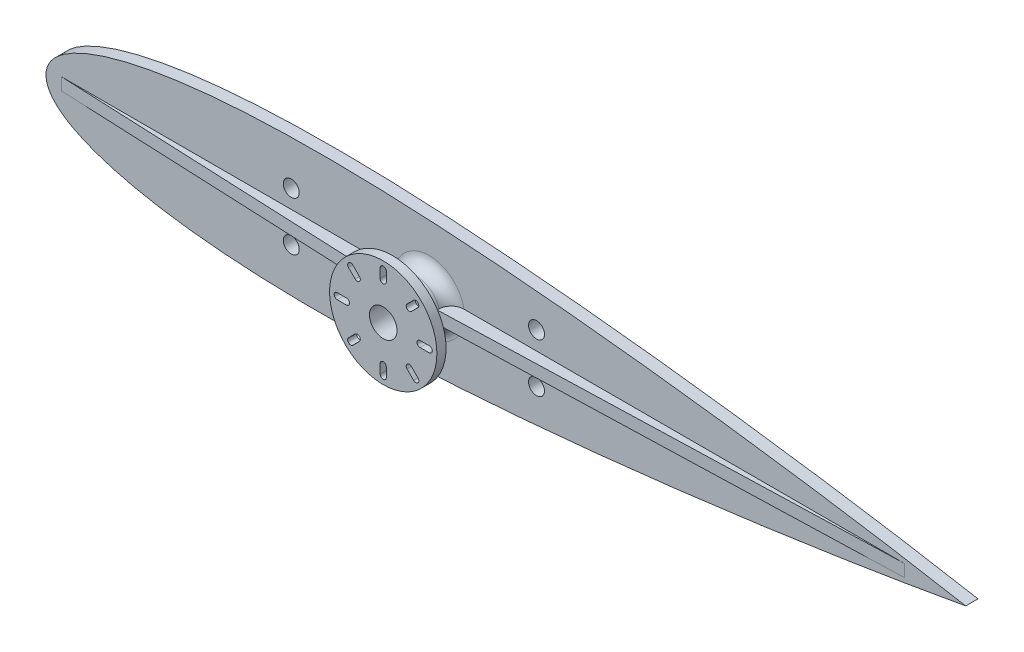
SolidWorks part; units mm, degrees
ref_plane "前视基准面" through (0, 0, 0) normal (0, 0, 1) x (1, 0, 0)
ref_plane "上视基准面" through (0, 0, 0) normal (0, 1, 0) x (1, 0, 0)
ref_plane "右视基准面" through (0, 0, 0) normal (1, 0, 0) x (0, 0, -1)
sketch "草图1" plane through (0, 0, 0) normal (0, 0, 1) x (1, 0, 0)
  line L0 (0, 0) -> (300, 0) construction
  circle A0 centre (125, 0) radius 4.5
  circle A1 centre (80, -8) radius 2.6
  circle A2 centre (160, -8) radius 2.6
  circle A3 centre (80, 8) radius 2.6
  circle A4 centre (160, 8) radius 2.6
  spline S0 degree 4 poles (0, 0) (-0.0001, -0.3264) (0.031, -0.854) (0.1504, -1.6168) (0.4487, -2.6089) (0.8484, -3.53) (1.4338, -4.5344) (2.2636, -5.6397) (3.4568, -6.8967) (5.2259, -8.3759) (7.9066, -10.1418) (11.9899, -12.2256) (18.3217, -14.6656) (27.8261, -17.3002) (41.9741, -19.921) (60.222, -21.8105) (78.6241, -22.5522) (95.989, -22.5497) (113.3459, -22.1022) (130.6895, -21.2711) (148.0103, -20.055) (165.3063, -18.538) (179.7033, -17.1021) (191.211, -15.8592) (201.272, -14.6957) (209.8891, -13.6473) (217.0668, -12.7405) (222.8049, -11.9958) (229.9776, -11.0404) (238.5739, -9.8566) (248.6055, -8.4182) (258.6114, -6.9148) (267.2017, -5.5723) (274.3229, -4.4249) (280.0727, -3.4754) (285.7008, -2.5255) (290.8293, -1.6369) (294.8732, -0.9241) (299.0931, -0.1658) (301.6957, 0.3078) (305.9109, 1.0842) (309.2256, 1.7092) (313.2454, 2.4742) (316.8292, 3.1721) (320.6864, 3.9322) (324.3505, 4.6701) (327.2182, 5.2551) (329.0543, 5.6359) (330.002, 5.8328) knots 0 0 0 0 0 0.003841 0.006235 0.009072 0.012193 0.015657 0.019917 0.025339 0.032593 0.042799 0.057705 0.079311 0.112503 0.158973 0.227236 0.2955 0.329632 0.363764 0.432028 0.500292 0.534424 0.568556 0.602688 0.63682 0.653886 0.670952 0.688018 0.705084 0.739215 0.773347 0.807479 0.824545 0.841611 0.858677 0.875743 0.892809 0.901342 0.909875 0.921141 0.932406 0.943672 0.954938 0.966203 0.977469 0.988734 1 1 1 1 1 construction
  spline S1 degree 4 poles (0, 0) (-0.0001, -0.3264) (0.031, -0.854) (0.1504, -1.6168) (0.4487, -2.6089) (0.8484, -3.53) (1.4338, -4.5344) (2.2636, -5.6397) (3.4568, -6.8967) (5.2259, -8.3759) (7.9066, -10.1418) (11.9899, -12.2256) (18.3217, -14.6656) (27.8261, -17.3002) (41.9741, -19.921) (60.222, -21.8105) (78.6241, -22.5522) (95.989, -22.5497) (113.3459, -22.1022) (130.6895, -21.2711) (148.0103, -20.055) (165.3063, -18.538) (179.7033, -17.1021) (191.211, -15.8592) (201.272, -14.6957) (209.8891, -13.6473) (217.0668, -12.7405) (222.8049, -11.9958) (229.9776, -11.0404) (238.5739, -9.8566) (248.6055, -8.4182) (258.6114, -6.9148) (267.2017, -5.5723) (274.3229, -4.4249) (280.0727, -3.4754) (285.7008, -2.5255) (290.8293, -1.6369) (294.8732, -0.9241) (298.0459, -0.354) (299.3524, -0.1177) (300, 0) knots 0 0 0 0 0 0.003841 0.006235 0.009072 0.012193 0.015657 0.019917 0.025339 0.032593 0.042799 0.057705 0.079311 0.112503 0.158973 0.227236 0.2955 0.329632 0.363764 0.432028 0.500292 0.534424 0.568556 0.602688 0.63682 0.653886 0.670952 0.688018 0.705084 0.739215 0.773347 0.807479 0.824545 0.841611 0.858677 0.875743 0.892809 0.901342 0.909875 0.909875 0.909875 0.909875 0.909875
  spline S2 degree 4 poles (0, 0) (-0.0001, 0.3264) (0.031, 0.854) (0.1504, 1.6168) (0.4487, 2.6089) (0.8484, 3.53) (1.4338, 4.5344) (2.2636, 5.6397) (3.4568, 6.8967) (5.2259, 8.3759) (7.9066, 10.1418) (11.9899, 12.2256) (18.3217, 14.6656) (27.8261, 17.3002) (41.9741, 19.921) (60.222, 21.8105) (78.6241, 22.5522) (95.989, 22.5497) (113.3459, 22.1022) (130.6895, 21.2711) (148.0103, 20.055) (165.3063, 18.538) (179.7033, 17.1021) (191.211, 15.8592) (201.272, 14.6957) (209.8891, 13.6473) (217.0668, 12.7405) (222.8049, 11.9958) (229.9776, 11.0404) (238.5739, 9.8566) (248.6055, 8.4182) (258.6114, 6.9148) (267.2017, 5.5723) (274.3229, 4.4249) (280.0727, 3.4754) (285.7008, 2.5255) (290.8293, 1.6369) (294.8732, 0.9241) (298.0459, 0.354) (299.3524, 0.1177) (300, 0) knots 0 0 0 0 0 0.003841 0.006235 0.009072 0.012193 0.015657 0.019917 0.025339 0.032593 0.042799 0.057705 0.079311 0.112503 0.158973 0.227236 0.2955 0.329632 0.363764 0.432028 0.500292 0.534424 0.568556 0.602688 0.63682 0.653886 0.670952 0.688018 0.705084 0.739215 0.773347 0.807479 0.824545 0.841611 0.858677 0.875743 0.892809 0.901342 0.909875 0.909875 0.909875 0.909875 0.909875
  dimension "D2" = 9
  dimension "D3" = 5.2
  dimension "D6" = 5.2
  dimension "D1" = 125
  dimension "D4" = 8
  dimension "D5" = 80
  dimension "D7" = 8
  dimension "D8" = 80
extrude "凸台-拉伸1" add sketch "草图1" along normal blind 4
sketch "草图2" plane through (0, 0, 4) normal (0, 0, 1) x (1, 0, 0)
  circle A0 centre (125, 0) radius 4.5
  circle A1 centre (125, 0) radius 7.5
  dimension "D1" = 15
  dimension "D2" = 9
extrude "凸台-拉伸2" add sketch "草图2" along normal blind 12
sketch "草图4" plane through (0, 0, 0) normal (0, 1, 0) x (1, 0, 0)
  line L0 (119.5, -9) -> (5, -4)
  line L2 (117.5, -4) -> (132.5, -4) construction
  dimension "D1" = 5
  dimension "D2" = 5
rib "筋7" sketch "草图4" sketch "草图4" thickness 4 extrusion direction parallel to sketch draft on no parameters "D1"=4
sketch "草图5" plane through (0, 0, 0) normal (0, 1, 0) x (1, 0, 0)
  line L0 (130.643, -8.6424) -> (280, -4)
  dimension "D1" = 20
  dimension "D2" = 5
rib "筋8" sketch "草图5" sketch "草图5" thickness 4 extrusion direction parallel to sketch draft on no parameters "D1"=4
fillet "圆角1" radius 4 2 edges at (125, 7.5, 4) (125, -7.5, 4)
sketch "草图6" plane through (0, 0, 16) normal (0, 0, 1) x (1, 0, 0)
  line L0 (144.3585, 0) -> (103.1927, 0) construction
  line L1 (125, -21.9345) -> (125, 24.2499) construction
  line L2 (140.3184, 15.3184) -> (125, 0) construction
  line L3 (125, 0) -> (110.0373, -14.9627) construction
  line L4 (125, 0) -> (139.7777, -14.7777) construction
  line L5 (125, 0) -> (109.1008, 15.8992) construction
  line L6 (140, 1) -> (137, 1)
  line L7 (140, -1) -> (137, -1)
  line L8 (110, -1) -> (113, -1)
  line L9 (110, 1) -> (113, 1)
  line L10 (126, -15) -> (126, -12)
  line L11 (124, -15) -> (124, -12)
  line L12 (124, 15) -> (124, 12)
  line L13 (126, 15) -> (126, 12)
  line L14 (125, 0) -> (145.3659, 8.4358) construction
  line L15 (134.8995, 11.3137) -> (132.7782, 9.1924)
  line L16 (136.3137, 9.8995) -> (134.1924, 7.7782)
  line L17 (113.6863, 9.8995) -> (115.8076, 7.7782)
  line L18 (115.1005, 11.3137) -> (117.2218, 9.1924)
  line L19 (113.6863, -9.8995) -> (115.8076, -7.7782)
  line L20 (115.1005, -11.3137) -> (117.2218, -9.1924)
  line L21 (136.3137, -9.8995) -> (134.1924, -7.7782)
  line L22 (134.8995, -11.3137) -> (132.7782, -9.1924)
  circle A0 centre (125, 0) radius 4.5
  circle A1 centre (125, 0) radius 17.5
  arc A2 (140, -1) -> (140, 1) centre (140, 0) ccw
  arc A3 (137, 1) -> (137, -1) centre (137, 0) ccw
  arc A4 (113, 1) -> (113, -1) centre (113, 0) cw
  arc A5 (110, -1) -> (110, 1) centre (110, 0) cw
  arc A6 (124, -12) -> (126, -12) centre (125, -12) cw
  arc A7 (126, -15) -> (124, -15) centre (125, -15) cw
  arc A8 (126, 12) -> (124, 12) centre (125, 12) cw
  arc A9 (124, 15) -> (126, 15) centre (125, 15) cw
  arc A10 (134.1924, 7.7782) -> (132.7782, 9.1924) centre (133.4853, 8.4853) cw
  arc A11 (134.8995, 11.3137) -> (136.3137, 9.8995) centre (135.6066, 10.6066) cw
  arc A12 (115.8076, 7.7782) -> (117.2218, 9.1924) centre (116.5147, 8.4853) ccw
  arc A13 (115.1005, 11.3137) -> (113.6863, 9.8995) centre (114.3934, 10.6066) ccw
  arc A14 (115.1005, -11.3137) -> (113.6863, -9.8995) centre (114.3934, -10.6066) cw
  arc A15 (115.8076, -7.7782) -> (117.2218, -9.1924) centre (116.5147, -8.4853) cw
  arc A16 (134.8995, -11.3137) -> (136.3137, -9.8995) centre (135.6066, -10.6066) ccw
  arc A17 (134.1924, -7.7782) -> (132.7782, -9.1924) centre (133.4853, -8.4853) ccw
  dimension "D1" = 35
  dimension "D7" = 22.5
  dimension "D8" = 2
  dimension "D2" = 45
  dimension "D3" = 45
  dimension "D4" = 45
  dimension "D5" = 45
  dimension "D6" = 15
  dimension "D9" = 12
extrude "凸台-拉伸3" add sketch "草图6" along normal blind 3
